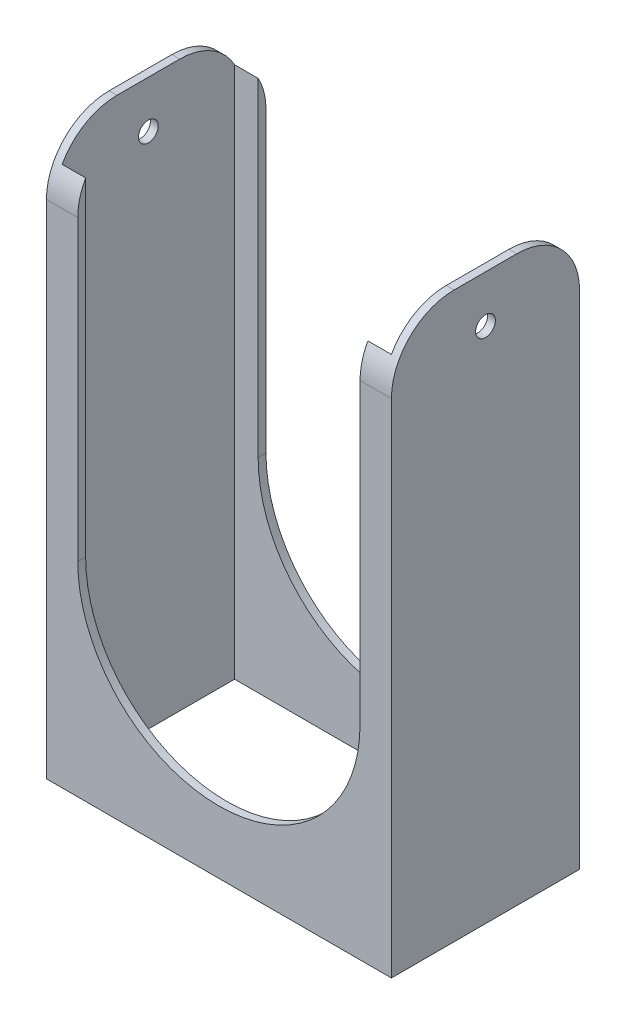
SolidWorks part; units mm, degrees
ref_plane "Front Plane" through (0, 0, 0) normal (0, 0, 1) x (1, 0, 0)
ref_plane "Top Plane" through (0, 0, 0) normal (0, 1, 0) x (1, 0, 0)
ref_plane "Right Plane" through (0, 0, 0) normal (1, 0, 0) x (0, 0, -1)
sketch "Sketch1" plane through (0, 0, 0) normal (0, 1, 0) x (1, 0, 0)
  line L0 (-66.675, -34.925) -> (-66.675, 34.925)
  line L1 (-69.85, -38.1) -> (69.85, -38.1)
  line L2 (-69.85, -38.1) -> (-69.85, 38.1)
  line L3 (-69.85, 38.1) -> (69.85, 38.1)
  line L4 (69.85, -38.1) -> (69.85, 38.1)
  line L5 (-69.85, -38.1) -> (69.85, 38.1) construction
  line L6 (-69.85, 38.1) -> (69.85, -38.1) construction
  line L7 (-66.675, 34.925) -> (66.675, 34.925)
  line L8 (66.675, -34.925) -> (66.675, 34.925)
  line L9 (-66.675, -34.925) -> (66.675, -34.925)
  point P0 (0, 0)
  dimension "D1" = 139.7
  dimension "D2" = 76.2
  dimension "D3" = 3.175
extrude "Boss-Extrude1" add sketch "Sketch1" along normal blind 228.6
sketch "Sketch2" plane through (69.85, 0, 0) normal (1, 0, 0) x (0, 0, -1)
  line L0 (-38.1, 228.6) -> (38.1, 228.6) construction
  line L1 (-38.1, 228.6) -> (-38.1, 0) construction
  line L2 (38.1, 228.6) -> (38.1, 0) construction
  line L3 (-38.1, 203.2) -> (-38.1, 228.6)
  line L4 (-38.1, 228.6) -> (-12.7, 228.6)
  line L5 (12.7, 228.6) -> (38.1, 228.6)
  line L6 (38.1, 228.6) -> (38.1, 203.2)
  circle A0 centre (0, 209.55) radius 4
  arc A1 (-38.1, 203.2) -> (-12.7, 228.6) centre (-12.7, 203.2) cw
  arc A2 (12.7, 228.6) -> (38.1, 203.2) centre (12.7, 203.2) cw
  dimension "D1" = 8
  dimension "D3" = 25.4
  dimension "D2" = 19.05
extrude "Cut-Extrude1" cut sketch "Sketch2" against normal through all
sketch "Sketch3" plane through (0, 0, 38.1) normal (0, 0, 1) x (1, 0, 0)
  line L2 (-57.15, 82.55) -> (-57.15, 228.6)
  line L3 (-69.85, 228.6) -> (69.85, 228.6) construction
  line L4 (-57.15, 228.6) -> (57.15, 228.6)
  line L5 (57.15, 228.6) -> (57.15, 82.55)
  line L6 (-69.85, 203.2) -> (-69.85, 0) construction
  line L9 (-57.15, 82.55) -> (-69.85, 82.55) construction
  line L10 (57.15, 82.55) -> (69.85, 82.55) construction
  line L11 (69.85, 203.2) -> (69.85, 0) construction
  line L12 (-69.85, 0) -> (69.85, 0) construction
  arc A0 (-57.15, 82.55) -> (57.15, 82.55) centre (0, 82.55) ccw
  point P5 (0, 0)
  dimension "D1" = 12.7
  dimension "D2" = 25.4
extrude "Cut-Extrude2" cut sketch "Sketch3" against normal through all both and the other way through all
